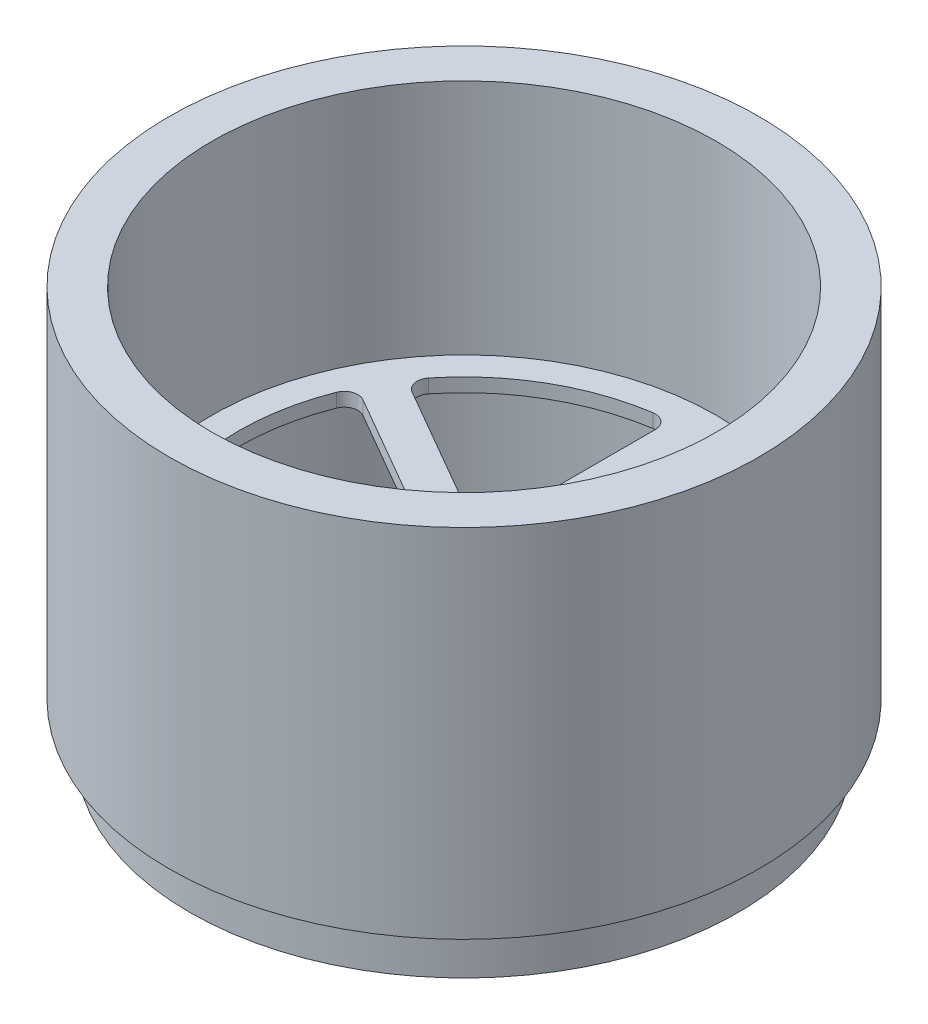
SolidWorks part; units mm, degrees
material "6061-T6 (SS)"
ref_plane "Front Plane" through (0, 0, 0) normal (0, 0, 1) x (1, 0, 0)
ref_plane "Top Plane" through (0, 0, 0) normal (0, 1, 0) x (1, 0, 0)
ref_plane "Right Plane" through (0, 0, 0) normal (1, 0, 0) x (0, 0, -1)
other "Center of Mass"
sketch "Sketch1" plane through (0, 0, 0) normal (0, 1, 0) x (1, 0, 0)
  circle A0 centre (0, 0) radius 21.5
  circle A1 centre (0, 0) radius 18.38
extrude "Boss-Extrude1" add sketch "Sketch1" along normal blind 29.5
ref_plane "Plane1" through (0, 11.2, 0) normal (0, -1, 0) x (-1, 0, 0)
sketch "Sketch3" plane through (0, 11.2, 0) normal (0, -1, 0) x (-1, 0, 0)
  circle A0 centre (0, 0) radius 21.5
extrude "Boss-Extrude2" add sketch "Sketch3" against normal blind 1
sketch "Sketch4" plane through (0, 11.2, 0) normal (0, -1, 0) x (-1, 0, 0)
  circle A0 centre (0, 0) radius 0.75
  circle A1 centre (0, 0) radius 2
extrude "Boss-Extrude3" add sketch "Sketch4" along normal blind 3.8
sketch "Sketch5" plane through (0, 0, 0) normal (0, 1, 0) x (1, 0, 0)
  circle A0 centre (0, 0) radius 20
extrude "Cut-Extrude1" cut sketch "Sketch5" along normal blind 3.5 flip side to cut
sketch "Sketch6" plane through (0, 11.2, 0) normal (0, -1, 0) x (-1, 0, 0)
  line L0 (1.3115, -4.359) -> (1.3115, -15.2454)
  line L1 (0, 0) -> (8.2098, -14.2199) construction
  line L2 (3.1192, -3.3153) -> (12.5472, -8.7585)
  circle A0 centre (0, 0) radius 16.4197 construction
  circle A1 centre (0, 0) radius 3.9339 construction
  arc A2 (2.4614, -16.2341) -> (12.8285, -10.2487) centre (0, 0) ccw
  arc A3 (1.843, -3.4755) -> (2.0883, -3.3339) centre (0, 0) ccw
  arc A4 (1.3115, -15.2454) -> (2.4614, -16.2341) centre (2.3115, -15.2454) ccw
  arc A5 (12.5472, -8.7585) -> (12.8285, -10.2487) centre (12.0472, -9.6246) cw
  arc A6 (3.1192, -3.3153) -> (2.0883, -3.3339) centre (2.6192, -4.1813) ccw
  arc A7 (1.3115, -4.359) -> (1.843, -3.4755) centre (2.3115, -4.359) cw
  point P13 (1.3115, -16.3672)
  point P14 (13.5187, -9.3194)
  point P17 (2.5562, -2.9902)
  point P20 (1.3115, -3.7089)
  dimension "D1" = 1
  dimension "D2" = 1
  dimension "D3" = 1
  dimension "D4" = 1
extrude "Cut-Extrude2" cut sketch "Sketch6" against normal up to next
pattern_circular "CirPattern1" count 6 over 360 about axis through (0, 0, 0) along (0, 1, 0) of "Cut-Extrude2"
